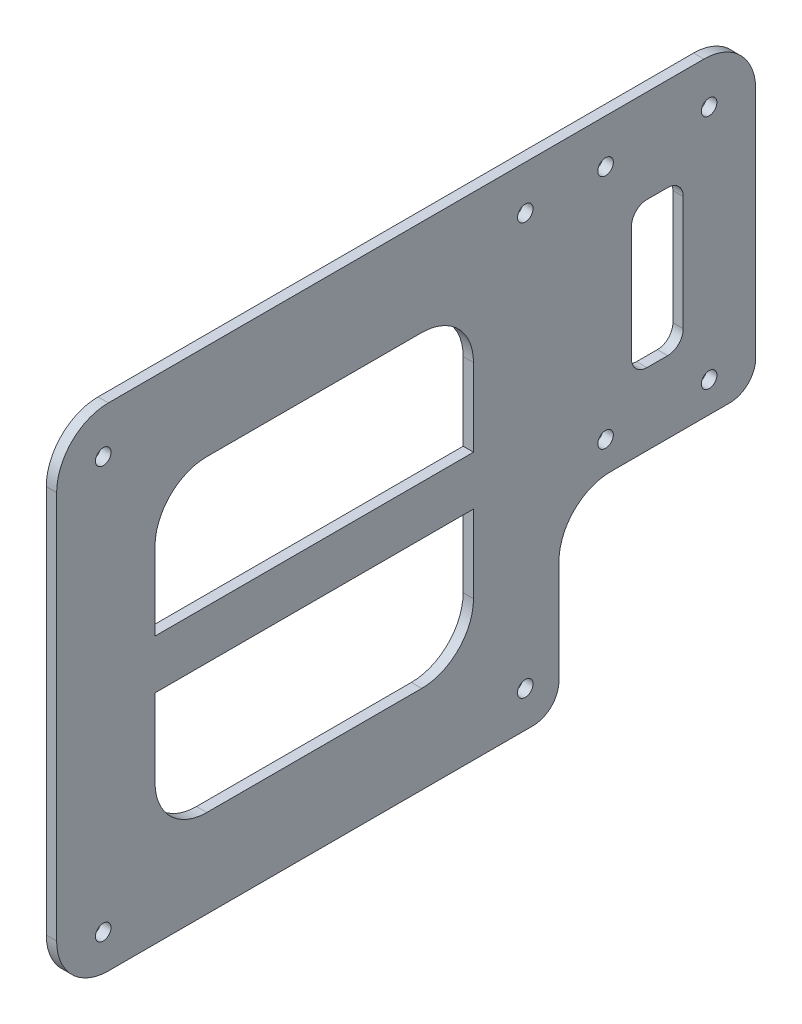
SolidWorks part; units mm, degrees
ref_plane "Front Plane" through (0, 0, 0) normal (0, 0, 1) x (1, 0, 0)
ref_plane "Top Plane" through (0, 0, 0) normal (0, 1, 0) x (1, 0, 0)
ref_plane "Right Plane" through (0, 0, 0) normal (1, 0, 0) x (0, 0, -1)
sketch "Sketch2" plane through (0, 0, 0) normal (1, 0, 0) x (0, 0, -1)
  line L0 (284.7988, 42) -> (346.2988, 42)
  line L1 (390.7988, 95) -> (275.7988, 95)
  line L2 (400.7988, 85) -> (400.7988, 40)
  line L3 (357.7988, 0) -> (275.7988, 0)
  line L4 (265.7988, 85) -> (265.7988, 10)
  line L5 (336.2988, 76.5) -> (294.7988, 76.5)
  line L6 (346.2988, 66.5) -> (346.2988, 51.5)
  line L7 (336.2988, 17) -> (294.7988, 17)
  line L8 (284.7988, 66.5) -> (284.7988, 51.5)
  line L9 (383.7988, 77) -> (379.7988, 77)
  line L10 (386.7988, 74) -> (386.7988, 51.9)
  line L11 (383.7988, 48.9) -> (379.7988, 48.9)
  line L12 (376.7988, 74) -> (376.7988, 51.9)
  line L13 (284.7988, 51.5) -> (346.2988, 51.5)
  line L14 (284.7988, 42) -> (284.7988, 27)
  line L15 (346.2988, 42) -> (346.2988, 27)
  line L16 (395.7988, 35) -> (372.7988, 35)
  line L17 (362.7988, 25) -> (362.7988, 5)
  arc A0 (372.7988, 35) -> (362.7988, 25) centre (372.7988, 25) ccw
  circle A1 centre (356.2988, 86.5) radius 1.5 construction
  circle A2 centre (274.7988, 86.5) radius 1.5 construction
  circle A3 centre (371.7988, 86.5) radius 1.5
  circle A4 centre (274.7988, 7) radius 1.5 construction
  arc A5 (346.2988, 27) -> (336.2988, 17) centre (336.2988, 27) cw
  arc A6 (294.7988, 17) -> (284.7988, 27) centre (294.7988, 27) cw
  arc A7 (294.7988, 76.5) -> (284.7988, 66.5) centre (294.7988, 66.5) ccw
  arc A8 (346.2988, 66.5) -> (336.2988, 76.5) centre (336.2988, 66.5) ccw
  arc A9 (362.7988, 5) -> (357.7988, 0) centre (357.7988, 5) cw
  circle A10 centre (391.7988, 86.5) radius 1.5
  arc A11 (395.7988, 35) -> (400.7988, 40) centre (395.7988, 40) ccw
  circle A12 centre (391.7988, 40.9) radius 1.5
  circle A14 centre (371.7988, 40.9) radius 1.5
  circle A16 centre (356.2988, 7) radius 1.5 construction
  circle A17 centre (356.2988, 7) radius 1.5
  circle A18 centre (274.7988, 7) radius 1.5 construction
  circle A19 centre (274.7988, 7) radius 1.5
  circle A20 centre (274.7988, 86.5) radius 1.5 construction
  circle A21 centre (274.7988, 86.5) radius 1.5
  circle A22 centre (356.2988, 86.5) radius 1.5 construction
  circle A23 centre (356.2988, 86.5) radius 1.5
  circle A24 centre (391.7988, 89.5) radius 1.5 construction
  arc A25 (379.7988, 48.9) -> (376.7988, 51.9) centre (379.7988, 51.9) cw
  arc A26 (386.7988, 51.9) -> (383.7988, 48.9) centre (383.7988, 51.9) cw
  arc A27 (379.7988, 77) -> (376.7988, 74) centre (379.7988, 74) ccw
  arc A28 (383.7988, 77) -> (386.7988, 74) centre (383.7988, 74) cw
  arc A30 (390.7988, 95) -> (400.7988, 85) centre (390.7988, 85) cw
  arc A31 (275.7988, 0) -> (265.7988, 10) centre (275.7988, 10) cw
  arc A32 (275.7988, 95) -> (265.7988, 85) centre (275.7988, 85) ccw
  dimension "D3" = 10
  dimension "D4" = 10
  dimension "D5" = 10
  dimension "D6" = 10
  dimension "D7" = 10
  dimension "D8" = 60
  dimension "D9" = 8
  dimension "D10" = 5
  dimension "D11" = 5
  dimension "D13" = 3
  dimension "D16" = 97
  dimension "D17" = 3
  dimension "D18" = 3
  dimension "D19" = 3
  dimension "D20" = 3
  dimension "D21" = 9
  dimension "D22" = 8.5
  dimension "D23" = 10
  dimension "D24" = 5
  dimension "D25" = 45.6
  dimension "D1" = 95
  dimension "D2" = 135
  dimension "D12" = 8
  dimension "D14" = 25
  dimension "D15" = 25
extrude "Boss-Extrude1" add sketch "Sketch2" along normal blind 2
